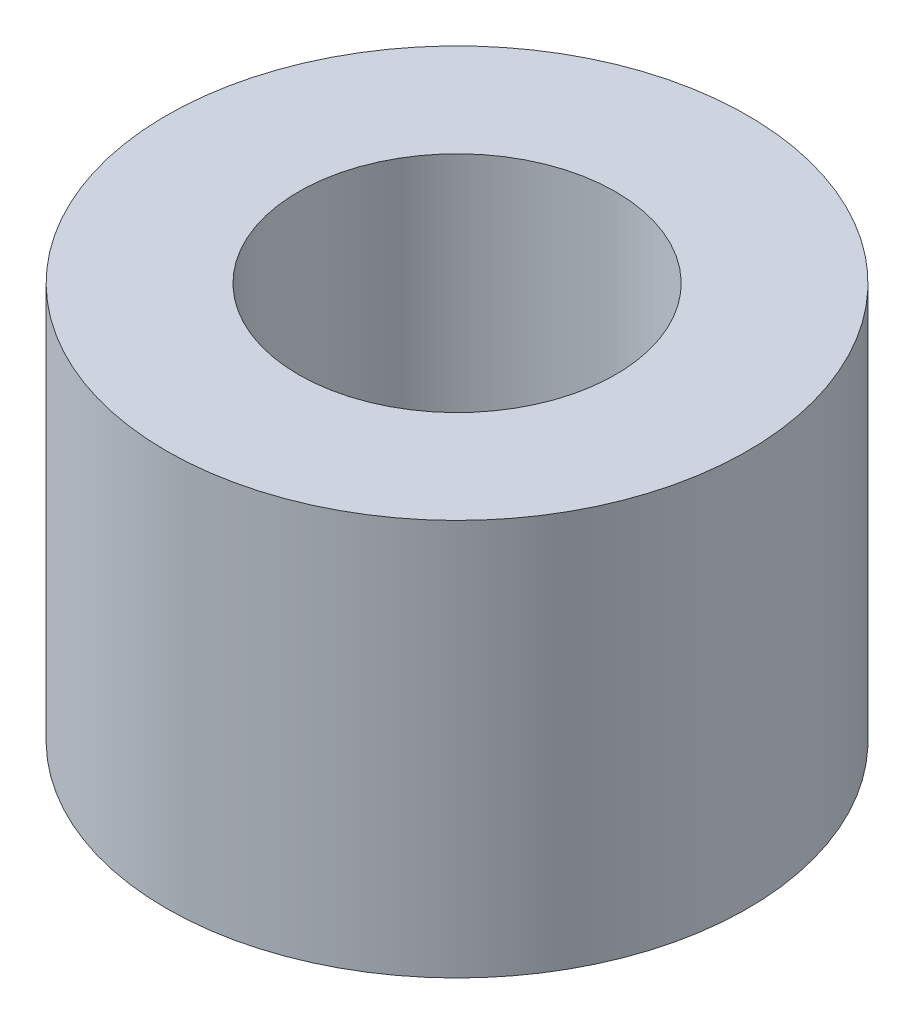
SolidWorks part; units mm, degrees
ref_plane "Alzado" through (0, 0, 0) normal (0, 0, 1) x (1, 0, 0)
ref_plane "Planta" through (0, 0, 0) normal (0, 1, 0) x (1, 0, 0)
ref_plane "Vista lateral" through (0, 0, 0) normal (1, 0, 0) x (0, 0, -1)
sketch "Sketch1" plane through (0, 0, 0) normal (0, 1, 0) x (1, 0, 0)
  circle A0 centre (0, 0) radius 6
  circle A1 centre (0, 0) radius 11
  dimension "D1" = 12
  dimension "D2" = 22
extrude "Boss-Extrude1" add sketch "Sketch1" along normal blind 15
